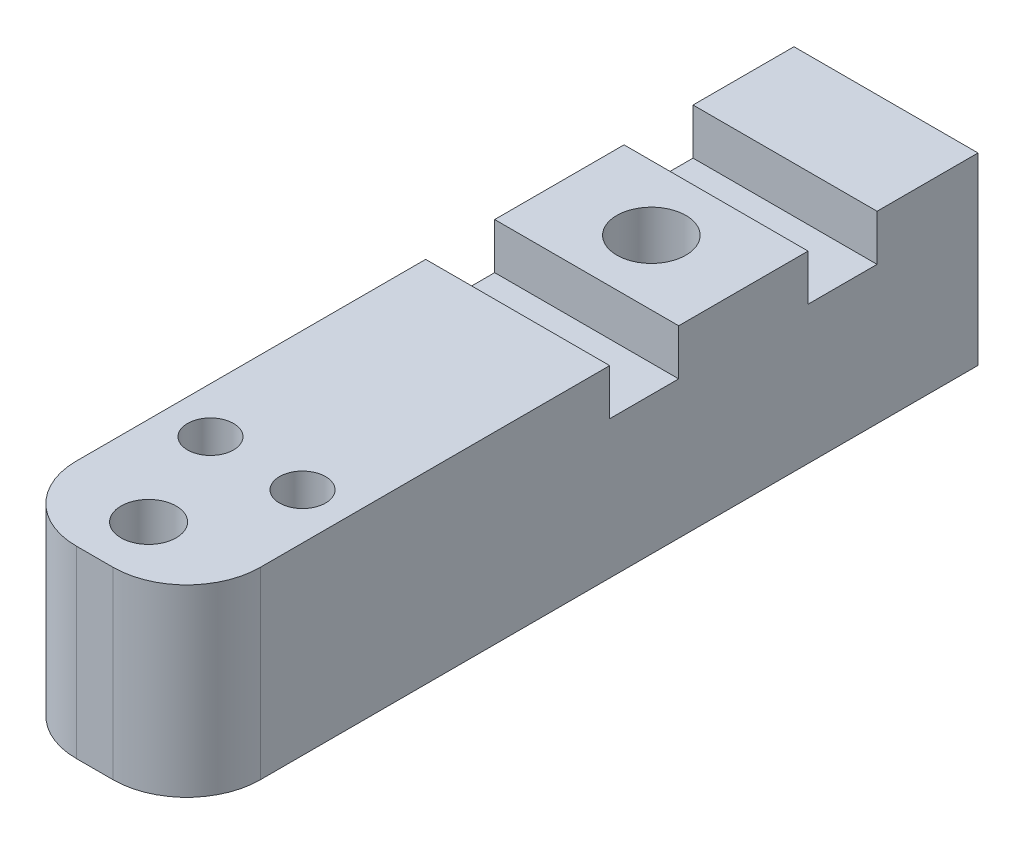
SolidWorks part; units mm, degrees
material "Plain Carbon Steel"
ref_plane "Front Plane" through (0, 0, 0) normal (0, 0, 1) x (1, 0, 0)
ref_plane "Top Plane" through (0, 0, 0) normal (0, 1, 0) x (1, 0, 0)
ref_plane "Right Plane" through (0, 0, 0) normal (1, 0, 0) x (0, 0, -1)
sketch "Sketch1" plane through (0, 0, 0) normal (0, 0, 1) x (1, 0, 0)
  line L1 (-25.4, 13.0503) -> (0, 13.0503)
  line L2 (-25.4, 13.0503) -> (-25.4, -12.3497)
  line L3 (-25.4, -12.3497) -> (0, -12.3497)
  line L4 (0, 13.0503) -> (0, -12.3497)
  dimension "D1" = 25.4
extrude "Boss-Extrude1" add sketch "Sketch1" along normal blind 109.22
sketch "Sketch2" plane through (0, 0, 0) normal (0, 0, -1) x (-1, 0, 0)
  circle A0 centre (12.7, 0) radius 2.54
  dimension "D1" = 5.08
extrude "Cut-Extrude1" cut sketch "Sketch2" against normal blind 17.78
sketch "Sketch3" plane through (0, 13.0503, 0) normal (0, 1, 0) x (1, 0, 0)
  line L0 (0, 0) -> (-25.4, 0) construction
  line L1 (0, -109.22) -> (0, 0) construction
  line L6 (-25.3934, -10.5699) -> (0, -20.0949) construction
  line L7 (-25.3934, -20.0949) -> (0, -10.5699) construction
  line L8 (-25.4, -109.22) -> (-25.4, 0) construction
  circle A0 centre (-12.7, -32.385) radius 4.7625
  point P4 (-12.6967, -15.3324)
  dimension "D1" = 9.525
  dimension "D2" = 32.385
  dimension "D3" = 12.7
extrude "Cut-Extrude2" cut sketch "Sketch3" against normal through all contours A0
sketch "Sketch7" plane through (0, 13.0503, 0) normal (0, 1, 0) x (1, 0, 0)
  line L2 (-25.4, -23.4575) -> (0, -23.4575)
  line L3 (-25.4, -109.22) -> (-25.4, 0) construction
  line L4 (0, -109.22) -> (0, 0) construction
  line L5 (0, -23.4575) -> (0, -13.9325)
  line L6 (0, -13.9325) -> (-25.4, -13.9325)
  line L7 (-25.4, -13.9325) -> (-25.4, -23.4575)
  line L9 (0, -41.3125) -> (0, -50.8375)
  line L10 (-25.4, -41.3125) -> (0, -41.3125)
  line L11 (-25.4, -50.8375) -> (-25.4, -41.3125)
  line L12 (0, -50.8375) -> (-25.4, -50.8375)
  dimension "D1" = 9.525
extrude "Cut-Extrude5" cut sketch "Sketch7" against normal blind 6.35
sketch "Sketch8" plane through (0, 13.0503, 0) normal (0, 1, 0) x (1, 0, 0)
  line L1 (1.054, -86.8843) -> (5.3888, -86.8843) construction
sketch "Sketch9" plane through (0, 13.0503, 0) normal (0, 1, 0) x (1, 0, 0)
  line L0 (1.054, -86.8843) -> (5.3888, -86.8843) construction
  circle A0 centre (-19.05, -86.8843) radius 3.175
  circle A1 centre (-6.35, -86.8843) radius 3.175
extrude "Cut-Extrude7" cut sketch "Sketch9" against normal through all
sketch "Sketch10" plane through (0, 13.0503, 0) normal (0, 1, 0) x (1, 0, 0)
  line L0 (0, -109.22) -> (-25.4, -109.22) construction
  circle A0 centre (-13.1359, -101.346) radius 3.81
  dimension "D2" = 7.62
  dimension "D1" = 7.874
extrude "Cut-Extrude8" cut sketch "Sketch10" against normal blind 16.51
fillet "Fillet1" radius 10.16 1 edges at (0, 0.3503, 109.22)
fillet "Fillet2" radius 10.16 1 edges at (-25.4, 0.3503, 109.22)
